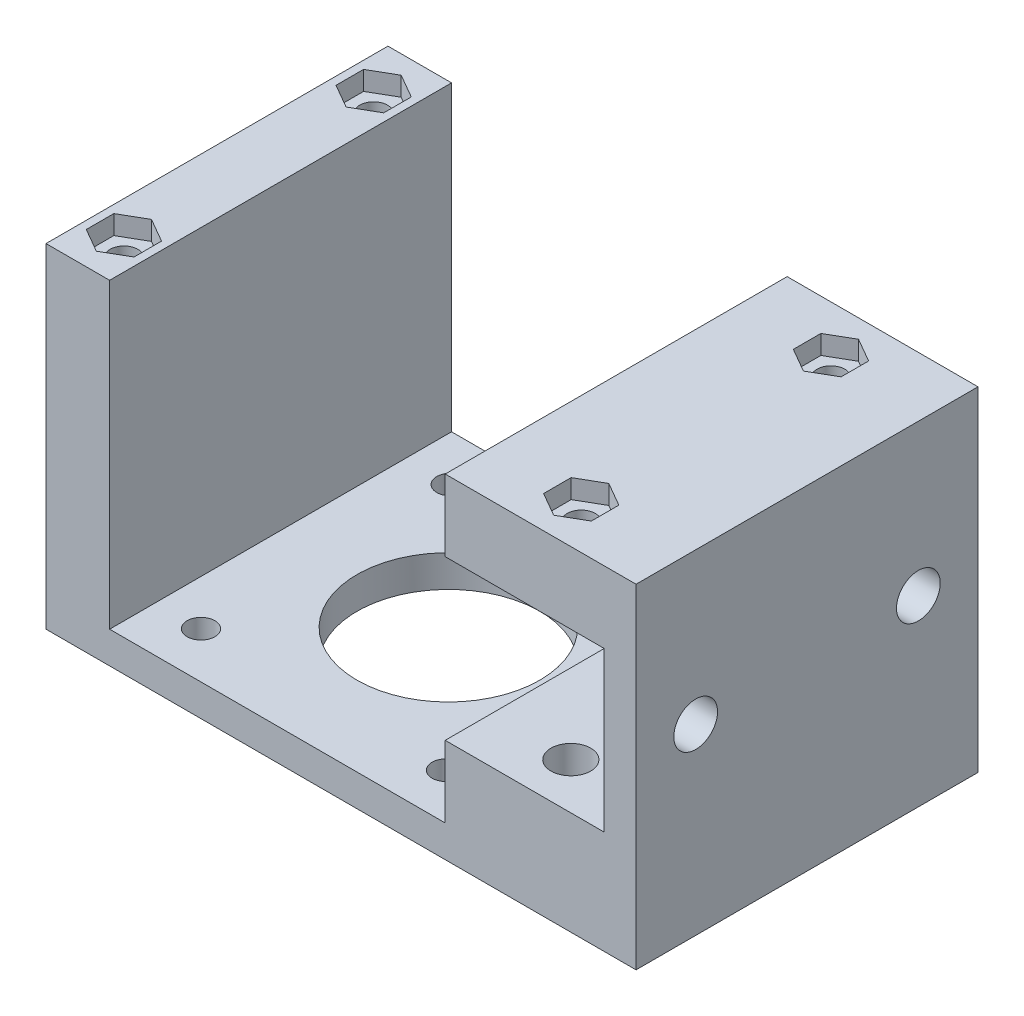
SolidWorks part; units mm, degrees
ref_plane "Front Plane" through (0, 0, 0) normal (0, 0, 1) x (1, 0, 0)
ref_plane "Top Plane" through (0, 0, 0) normal (0, 1, 0) x (1, 0, 0)
ref_plane "Right Plane" through (0, 0, 0) normal (1, 0, 0) x (0, 0, -1)
sketch "Sketch1" plane through (0, 0, 0) normal (0, 0, 1) x (1, 0, 0)
  line L1 (0, 0) -> (20, 0)
  line L3 (0, 20) -> (20, 20)
  line L4 (20, 0) -> (20, 20)
  line L6 (-50.2, 29) -> (-42.2, 29) construction
  line L11 (24, 33) -> (24, -13)
  line L12 (-42.2, -9) -> (0, -9)
  line L13 (-42.2, 29) -> (0, 29)
  line L15 (-50.2, 33) -> (-50.2, -13)
  line L16 (-50.2, 33) -> (24, 33)
  line L17 (-50.2, -13) -> (24, -13)
  line L18 (0, 29) -> (0, 20)
  line L21 (0, 0) -> (0, -9)
  line L22 (-42.2, -9) -> (-50.2, -8.4) construction
  line L24 (-42.2, 29) -> (-42.2, -9)
  dimension "D1" = 20
  dimension "D2" = 20
  dimension "D3" = 4
  dimension "D4" = 9
  dimension "D5" = 4
  dimension "D6" = 42.2
  dimension "D7" = 37.4
  dimension "D8" = 8
  dimension "D9" = 4
  dimension "D10" = 9
  dimension "D11" = 20
extrude "Boss-Extrude1" add sketch "Sketch1" along normal blind 43
sketch "Sketch2" plane through (0, -13, 0) normal (0, -1, 0) x (1, 0, 0)
  line L0 (0, 0) -> (-42.2, 43) construction
  line L1 (0, 0) -> (0, 43) construction
  line L2 (-50.2, 43) -> (24, 43) construction
  line L3 (0, 43) -> (-42.2, 0) construction
  line L4 (-36.5096, 37.2017) -> (-36.5096, 5.7983) construction
  line L5 (-5.6904, 5.7983) -> (-5.6904, 37.2017) construction
  line L6 (-42.2, 43) -> (-42.2, 0) construction
  line L7 (-50.2, 0) -> (24, 0) construction
  line L8 (-50.2, 43) -> (-50.2, 0) construction
  line L9 (20, 43) -> (20, 0) construction
  line L10 (24, 43) -> (24, 0) construction
  line L11 (0, 37.2017) -> (20, 37.2017) construction
  line L12 (0, 5.7983) -> (20, 5.7983) construction
  circle A0 centre (-21.1, 21.5) radius 11.5
  circle A1 centre (-36.5096, 37.2017) radius 1.75
  circle A2 centre (-5.6904, 5.7983) radius 1.75
  circle A3 centre (-36.5096, 5.7983) radius 1.75
  circle A4 centre (-5.6904, 37.2017) radius 1.75
  circle A7 centre (10, 37.2017) radius 2.5
  circle A8 centre (10, 5.7983) radius 2.5
  point P11 (-36.5096, 37.2017)
  point P12 (-5.6904, 5.7983)
  dimension "D1" = 23
  dimension "D4" = 3.5
  dimension "D5" = 3.5
  dimension "D6" = 3.5
  dimension "D7" = 3.5
  dimension "D9" = 4
  dimension "D10" = 5
  dimension "D11" = 5
  dimension "D2" = 22
  dimension "D3" = 22
  dimension "D8" = 8
extrude "Cut-Extrude1" cut sketch "Sketch2" against normal blind 20
sketch "Sketch3" plane through (0, 33, 0) normal (0, 1, 0) x (1, 0, 0)
  line L0 (0, 0) -> (0, -43) construction
  line L1 (24, -43) -> (-50.2, -43) construction
  line L2 (-42.2, 0) -> (0, -43) construction
  line L3 (0, 0) -> (-42.2, -43) construction
  line L4 (-36.5096, -5.7983) -> (-36.5096, -37.2017) construction
  line L5 (-36.5096, -37.2017) -> (-5.6904, -37.2017) construction
  line L6 (-5.6904, -5.7983) -> (-5.6904, -37.2017) construction
  line L7 (-36.5096, -5.7983) -> (-5.6904, -5.7983) construction
  line L8 (-42.2, 0) -> (-42.2, -43) construction
  line L9 (24, 0) -> (-50.2, 0) construction
  line L10 (-50.2, -43) -> (-50.2, 0) construction
  line L11 (-42.2, -5.7983) -> (-50.2, -5.7983) construction
  line L12 (-42.2, -37.2017) -> (-50.2, -37.2017) construction
  line L13 (0, -5.7983) -> (24, -5.7983) construction
  line L14 (24, -43) -> (24, 0) construction
  line L15 (0, -37.2017) -> (24, -37.2017) construction
  line L16 (11.3096, -5.7983) -> (11.3096, -37.2017) construction
  circle A0 centre (-36.5096, -5.7983) radius 3.1
  circle A1 centre (-5.6904, -5.7983) radius 3.1
  circle A2 centre (-5.6904, -37.2017) radius 3.1
  circle A3 centre (-36.5096, -37.2017) radius 3.1
  circle A4 centre (-46.2, -5.7983) radius 1.75
  circle A5 centre (-46.2, -37.2017) radius 1.75
  circle A6 centre (11.3096, -5.7983) radius 1.75
  circle A7 centre (11.3096, -37.2017) radius 1.75
  point P8 (-36.5096, -5.7983)
  point P10 (-21.1, -21.5)
  dimension "D2" = 6.2
  dimension "D3" = 6.2
  dimension "D4" = 6.2
  dimension "D5" = 6.2
  dimension "D7" = 3.5
  dimension "D8" = 3.5
  dimension "D9" = 3.5
  dimension "D10" = 3.5
  dimension "D1" = 22
  dimension "D6" = 8
  dimension "D11" = 17
extrude "Cut-Extrude2" cut sketch "Sketch3" against normal blind 15
ref_plane "Plane1" through (0, 29, 0) normal (0, 1, 0) x (1, 0, 0)
split "Split1" trim tools "Plane1" bodies to split 103 resulting bodies 106 107
sketch "Sketch4" plane through (0, 29, 0) normal (0, 1, 0) x (1, 0, 0)
  line L1 (-46.2, -2.3342) -> (-49.2, -4.0662)
  line L2 (-49.2, -4.0662) -> (-49.2, -7.5303)
  line L3 (-49.2, -7.5303) -> (-46.2, -9.2624)
  line L4 (-46.2, -9.2624) -> (-43.2, -7.5303)
  line L5 (-43.2, -7.5303) -> (-43.2, -4.0662)
  line L6 (-43.2, -4.0662) -> (-46.2, -2.3342)
  line L7 (-43.2, -35.4697) -> (-46.2, -33.7376)
  line L8 (-46.2, -33.7376) -> (-49.2, -35.4697)
  line L9 (-49.2, -35.4697) -> (-49.2, -38.9338)
  line L10 (-49.2, -38.9338) -> (-46.2, -40.6658)
  line L11 (-46.2, -40.6658) -> (-43.2, -38.9338)
  line L12 (-43.2, -38.9338) -> (-43.2, -35.4697)
  line L13 (14.3096, -4.0662) -> (11.3096, -2.3342)
  line L14 (11.3096, -2.3342) -> (8.3096, -4.0662)
  line L15 (8.3096, -4.0662) -> (8.3096, -7.5303)
  line L16 (8.3096, -7.5303) -> (11.3096, -9.2624)
  line L17 (11.3096, -9.2624) -> (14.3096, -7.5303)
  line L18 (14.3096, -7.5303) -> (14.3096, -4.0662)
  line L19 (14.3096, -35.4697) -> (11.3096, -33.7376)
  line L20 (11.3096, -33.7376) -> (8.3096, -35.4697)
  line L21 (8.3096, -35.4697) -> (8.3096, -38.9338)
  line L22 (8.3096, -38.9338) -> (11.3096, -40.6658)
  line L23 (11.3096, -40.6658) -> (14.3096, -38.9338)
  line L24 (14.3096, -38.9338) -> (14.3096, -35.4697)
  circle A0 centre (-46.2, -5.7983) radius 3 construction
  circle A1 centre (-46.2, -37.2017) radius 3 construction
  circle A2 centre (11.3096, -5.7983) radius 3 construction
  circle A3 centre (11.3096, -37.2017) radius 3 construction
  point P10 (-47.7, -39.7998)
  point P29 (9.8096, -8.3964)
  dimension "D1" = 6
  dimension "D2" = 6
  dimension "D3" = 6
  dimension "D4" = 6
extrude "Cut-Extrude3" cut sketch "Sketch4" against normal blind 2.4
sketch "Sketch5" plane through (24, 0, 0) normal (1, 0, 0) x (0, 0, -1)
  line L0 (0, 0) -> (-43, 0) construction
  line L1 (-43, -13) -> (-43, 29) construction
  line L2 (-43, 20) -> (0, 20) construction
  line L3 (0, -13) -> (0, 29) construction
  line L4 (-21.5, 20) -> (-21.5, 0) construction
  line L5 (-43, 10) -> (0, 10) construction
  circle A0 centre (-35.5, 10) radius 2.75
  circle A1 centre (-7.5, 10) radius 2.75
  point P17 (-21.5, 10)
  dimension "D2" = 5.5
  dimension "D3" = 5.5
  dimension "D1" = 20
extrude "Cut-Extrude4" cut sketch "Sketch5" against normal blind 12.4
delete or keep bodies "Body-Delete/Keep 1" type delete bodies bodies 106
